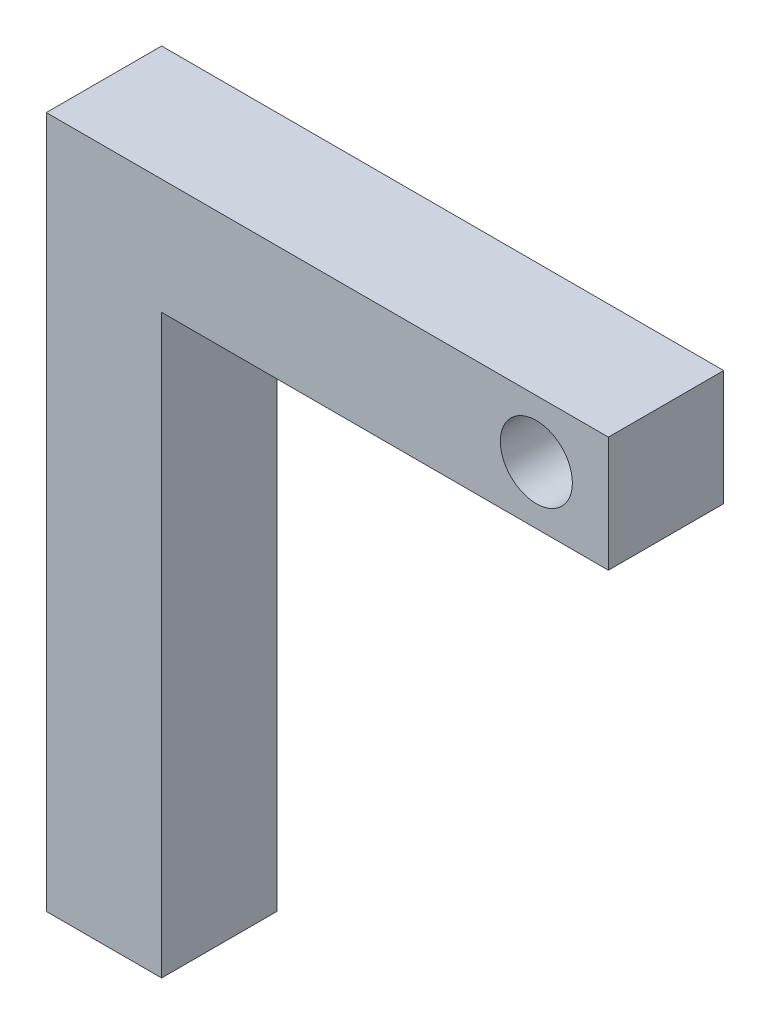
SolidWorks part; units mm, degrees
ref_plane "Front Plane" through (0, 0, 0) normal (0, 0, 1) x (1, 0, 0)
ref_plane "Top Plane" through (0, 0, 0) normal (0, 1, 0) x (1, 0, 0)
ref_plane "Right Plane" through (0, 0, 0) normal (1, 0, 0) x (0, 0, -1)
sketch "Sketch1" plane through (0, 0, 0) normal (0, 0, 1) x (1, 0, 0)
  line L0 (0, 892.9855) -> (0, 0) construction
  line L1 (0, 0) -> (1202.6614, 0) construction
  line L2 (0, 0) -> (0, 480)
  line L3 (0, 480) -> (390, 480)
  line L4 (390, 480) -> (390, 400)
  line L5 (390, 400) -> (80, 400)
  line L6 (80, 400) -> (80, 0)
  line L7 (80, 0) -> (0, 0)
  dimension "D1" = 390
  dimension "D3" = 80
  dimension "D4" = 80
  dimension "D5" = 400
extrude "Boss-Extrude1" add sketch "Sketch1" along normal blind 80
sketch "Sketch2" plane through (0, 0, 80) normal (0, 0, 1) x (1, 0, 0)
  line L0 (390, 440) -> (385.2259, 440) construction
  line L1 (390, 400) -> (390, 480) construction
  circle A0 centre (340, 440) radius 25
  dimension "D1" = 50
  dimension "D2" = 50
extrude "Cut-Extrude1" cut sketch "Sketch2" against normal blind 161
